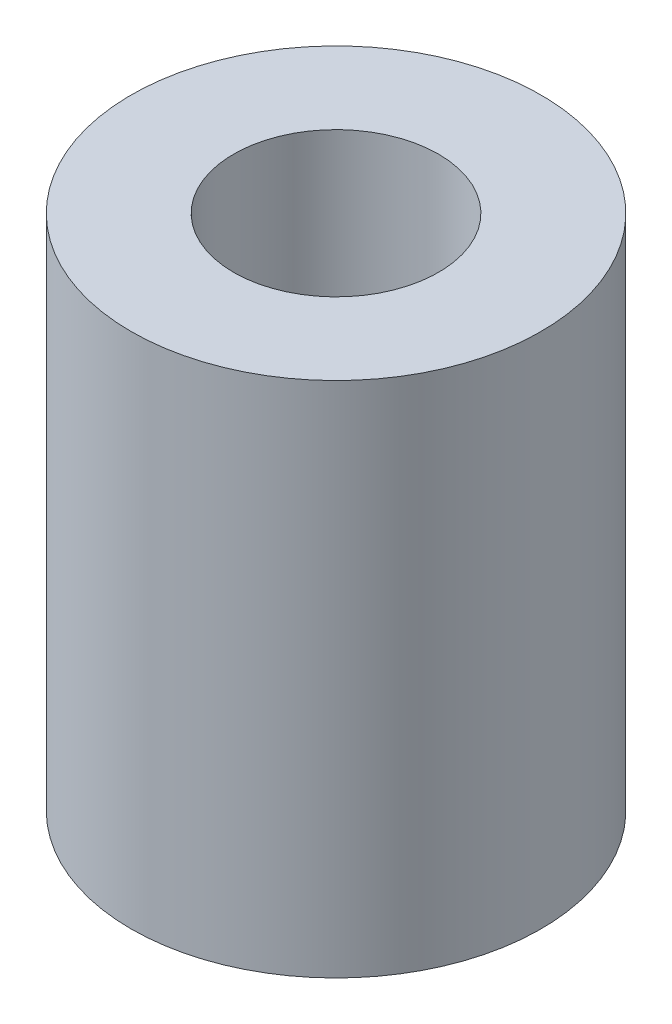
SolidWorks part; units mm, degrees
ref_plane "Front Plane" through (0, 0, 0) normal (0, 0, 1) x (1, 0, 0)
ref_plane "Top Plane" through (0, 0, 0) normal (0, 1, 0) x (1, 0, 0)
ref_plane "Right Plane" through (0, 0, 0) normal (1, 0, 0) x (0, 0, -1)
sketch "Sketch2" plane through (0, 0, 0) normal (0, 1, 0) x (1, 0, 0)
  circle A0 centre (0, 0) radius 1
  circle A1 centre (0, 0) radius 2
extrude "Boss-Extrude1" add sketch "Sketch2" along normal blind 5.05
